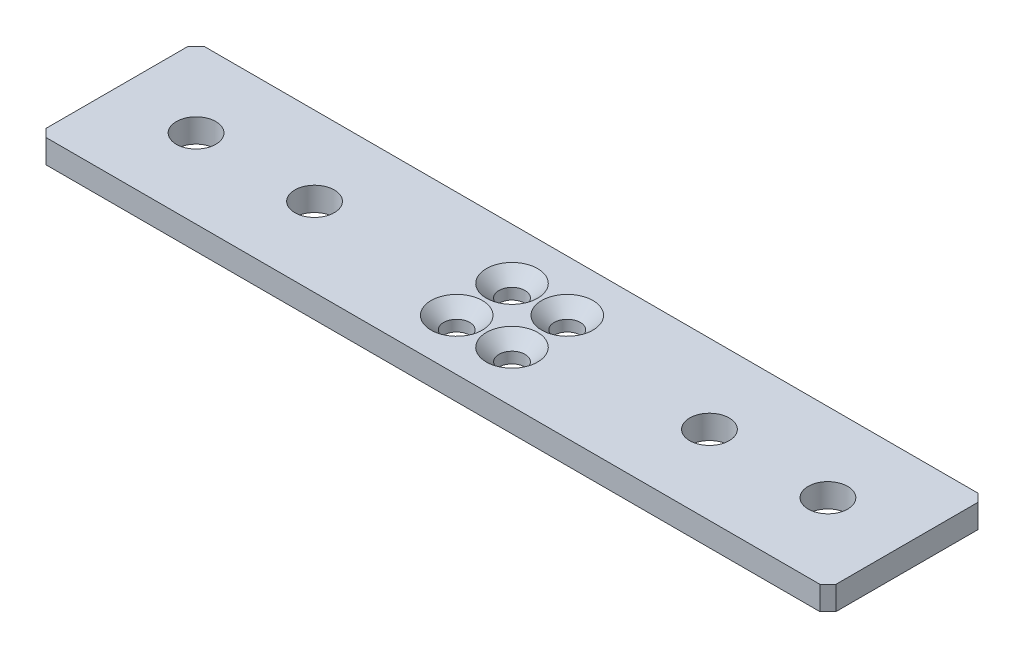
SolidWorks part; units mm, degrees
material "1023 Carbon Steel Sheet (SS)"
ref_plane "Front Plane" through (0, 0, 0) normal (0, 0, 1) x (1, 0, 0)
ref_plane "Top Plane" through (0, 0, 0) normal (0, 1, 0) x (1, 0, 0)
ref_plane "Right Plane" through (0, 0, 0) normal (1, 0, 0) x (0, 0, -1)
sketch "Sketch1" plane through (0, 0, 0) normal (0, 1, 0) x (1, 0, 0)
  line L0 (100, 20) -> (-100, 20)
  line L11 (0, -2.75) -> (0, 2.75) construction
  line L12 (-100, 20) -> (-100, -20)
  line L13 (-2.75, 0) -> (2.75, 0) construction
  line L14 (100, 20) -> (100, -20)
  line L15 (100, -20) -> (-100, -20)
  point P5 (0, -20)
  point P9 (0, 20)
  point P10 (100, 0)
  point P11 (-100, 0)
  dimension "D1" = 40
  dimension "D2" = 200
extrude "Boss-Extrude1" add sketch "Sketch1" along normal blind 6
hole_wizard "CSK for M6 Countersunk Flat Head Screw1" positions "Sketch6" profile "Sketch5" countersink size "M6" standard "ISO" end condition through all
sketch "Sketch6" plane through (0, 6, 0) normal (0, 1, 0) x (1, 0, 0)
  line L0 (0, -3.3) -> (0, 3.3) construction
  line L1 (-3.3, 0) -> (3.3, 0) construction
  point P0 (-7, 7)
  point P5 (7, 7)
  point P8 (7, -7)
  point P9 (-7, -7)
  dimension "D1" = 14
  dimension "D2" = 14
sketch "Sketch5" plane through (-7, 6, -7) normal (1, 0, 0) x (0, 0, 1)
  line L0 (0, 0) -> (0, 6)
  line L1 (0, 6) -> (3.3, 6)
  line L2 (3.3, 6) -> (3.3, 3.2)
  line L3 (3.3, 3.2) -> (6.5, 0)
  line L5 (6.5, 0) -> (0, 0)
  line L6 (-3.3, 3.2) -> (-6.5, 0) construction
  line L11 (0, -6.35) -> (0, 107.95) construction
  dimension "Thru Hole Dia." = 6.6
  dimension "Thru Hole Depth" = 6
  dimension "Near C'Sink Dia." = 13
  dimension "Near C'Sink Angle" = 90
chamfer "Chamfer1" distance 2 angle 45 4 edges at (100, 3, -20) (100, 3, 20) (-100, 3, 20) (-100, 3, -20)
sketch "Sketch8" plane through (0, 6, 0) normal (0, 1, 0) x (1, 0, 0)
  line L0 (-3.3, 0) -> (3.3, 0) construction
  line L1 (0, -3.3) -> (0, 3.3) construction
  circle A0 centre (-50, 0) radius 5
  circle A1 centre (-80, 0) radius 5
  dimension "D1" = 10
  dimension "D2" = 50
  dimension "D3" = 2
extrude "Cut-Extrude1" cut sketch "Sketch8" against normal through all
mirror "Mirror1" about plane through (0, 0, 0) normal (1, 0, 0) of "Cut-Extrude1"
